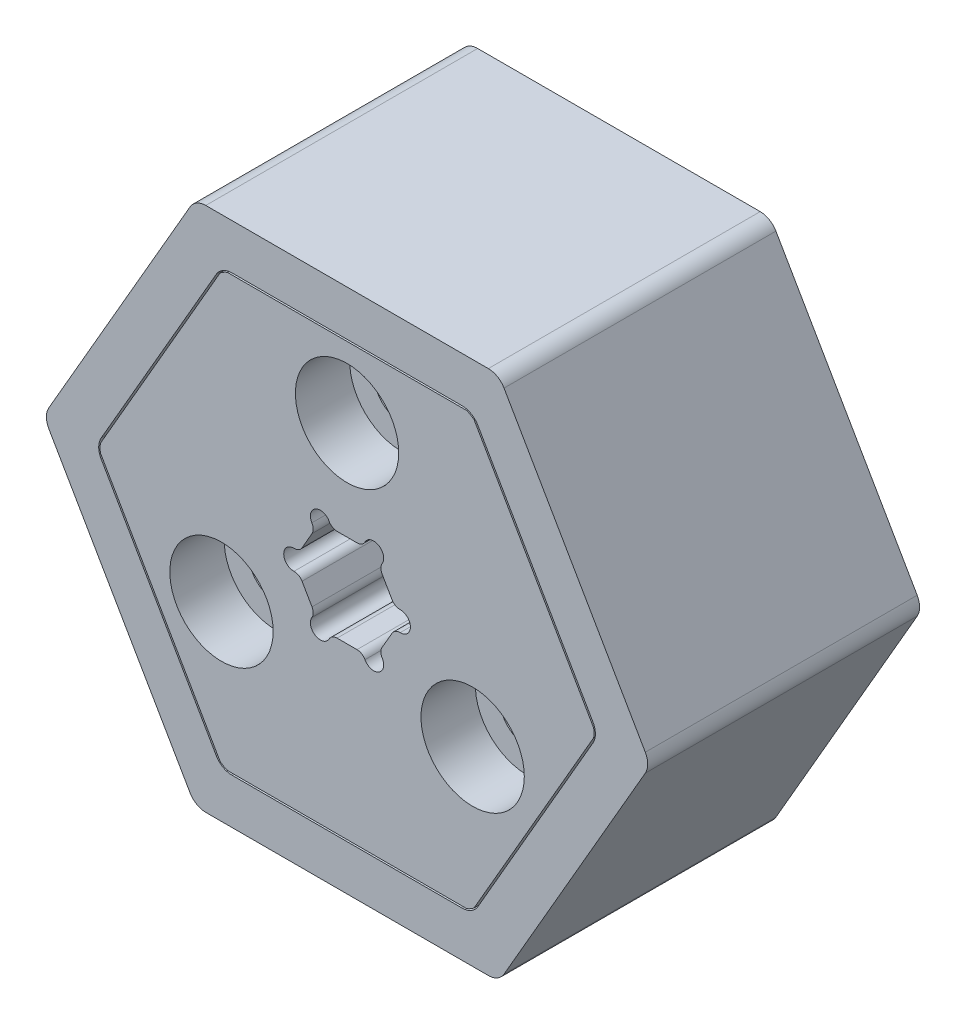
SolidWorks part; units mm, degrees
ref_plane "前视基准面" through (0, 0, 0) normal (0, 0, 1) x (1, 0, 0)
ref_plane "上视基准面" through (0, 0, 0) normal (0, 1, 0) x (1, 0, 0)
ref_plane "右视基准面" through (0, 0, 0) normal (1, 0, 0) x (0, 0, -1)
other "Configuration Table"
sketch "草图1" plane through (0, 0, 0) normal (0, 0, 1) x (1, 0, 0)
  line L0 (0, 6.5) -> (0, 0) construction
  line L1 (0, 0) -> (0, -6.5) construction
  line L3 (8.3716, 14.5) -> (-8.3716, 14.5)
  line L4 (-8.3716, 14.5) -> (-16.7432, 0)
  line L5 (-16.7432, 0) -> (-8.3716, -14.5)
  line L6 (-8.3716, -14.5) -> (8.3716, -14.5)
  line L7 (8.3716, -14.5) -> (16.7432, 0)
  line L8 (16.7432, 0) -> (8.3716, 14.5)
  line L9 (7.2169, 12.5) -> (-7.2169, 12.5)
  line L10 (-7.2169, 12.5) -> (-14.4338, 0)
  line L11 (-14.4338, 0) -> (-7.2169, -12.5)
  line L12 (-7.2169, -12.5) -> (7.2169, -12.5)
  line L13 (7.2169, -12.5) -> (14.4338, 0)
  line L14 (14.4338, 0) -> (7.2169, 12.5)
  circle A1 centre (0, 6.5) radius 1.5
  circle A2 centre (0, -6.5) radius 1.5
  circle A3 centre (0, 0) radius 14.5 construction
  circle A4 centre (0, 0) radius 12.5 construction
  dimension "D1" = 3
  dimension "D2" = 13
  dimension "D3" = 29
  dimension "D4" = 2
extrude "凸台-拉伸1" add sketch "草图1" along normal blind 2 contours L13 L14 L9 L10 L11 L12 A2 A1 | L7 L8 L3 L4 L5 L6 L14 L13 L12 L11 L10 L9
sketch "草图2" plane through (0, 0, 2) normal (0, 0, 1) x (1, 0, 0)
  line L1 (5.7735, 10) -> (-5.7735, 10)
  line L2 (-5.7735, 10) -> (-11.547, 0)
  line L3 (-11.547, 0) -> (-5.7735, -10)
  line L4 (-5.7735, -10) -> (5.7735, -10)
  line L5 (5.7735, -10) -> (11.547, 0)
  line L6 (11.547, 0) -> (5.7735, 10)
  line L7 (4.6188, 8) -> (-4.6188, 8)
  line L8 (-4.6188, 8) -> (-9.2376, 0)
  line L9 (-9.2376, 0) -> (-4.6188, -8)
  line L10 (-4.6188, -8) -> (4.6188, -8)
  line L11 (4.6188, -8) -> (9.2376, 0)
  line L12 (9.2376, 0) -> (4.6188, 8)
  circle A0 centre (0, 0) radius 10 construction
  circle A1 centre (0, 0) radius 8 construction
  dimension "D1" = 2
sketch "草图3" plane through (0, 0, 2) normal (0, 0, 1) x (1, 0, 0)
  line L1 (6.9282, 12) -> (-6.9282, 12)
  line L2 (-6.9282, 12) -> (-13.8564, 0)
  line L3 (-13.8564, 0) -> (-6.9282, -12)
  line L4 (-6.9282, -12) -> (6.9282, -12)
  line L5 (6.9282, -12) -> (13.8564, 0)
  line L6 (13.8564, 0) -> (6.9282, 12)
  line L12 (8.3716, -14.5) -> (16.7432, 0)
  line L13 (16.7432, 0) -> (8.3716, 14.5)
  line L14 (8.3716, 14.5) -> (-8.3716, 14.5)
  line L15 (-8.3716, 14.5) -> (-16.7432, 0)
  line L16 (-16.7432, 0) -> (-8.3716, -14.5)
  line L17 (-8.3716, -14.5) -> (8.3716, -14.5)
  line L18 (8.3716, -14.5) -> (16.7432, 0)
  line L19 (16.7432, 0) -> (8.3716, 14.5)
  line L20 (8.3716, 14.5) -> (-8.3716, 14.5)
  line L21 (-8.3716, 14.5) -> (-16.7432, 0)
  line L22 (-16.7432, 0) -> (-8.3716, -14.5)
  line L23 (-8.3716, -14.5) -> (8.3716, -14.5)
  circle A0 centre (0, 0) radius 12 construction
  dimension "D2" = 2.5
  dimension "D1" = 0
extrude "凸台-拉伸2" add sketch "草图3" along normal blind 13
sketch "草图4" plane through (0, 0, 2) normal (0, 0, 1) x (1, 0, 0)
  line L0 (0, 6.5) -> (0, -6.5) construction
  line L1 (3, 6.5) -> (3, -6.5)
  line L2 (-3, 6.5) -> (-3, -6.5)
  line L6 (13.8564, 0) -> (6.9282, 12)
  line L7 (6.9282, 12) -> (-6.9282, 12)
  line L8 (-6.9282, 12) -> (-13.8564, 0)
  line L9 (-13.8564, 0) -> (-6.9282, -12)
  line L10 (-6.9282, -12) -> (6.9282, -12)
  line L11 (6.9282, -12) -> (13.8564, 0)
  line L12 (13.8564, 0) -> (6.9282, 12)
  line L13 (6.9282, 12) -> (-6.9282, 12)
  line L14 (-6.9282, 12) -> (-13.8564, 0)
  line L15 (-13.8564, 0) -> (-6.9282, -12)
  line L16 (-6.9282, -12) -> (6.9282, -12)
  line L17 (6.9282, -12) -> (13.8564, 0)
  circle A1 centre (0, -6.5) radius 1.5
  circle A2 centre (0, -6.5) radius 1.5 construction
  circle A3 centre (0, 6.5) radius 1.5
  circle A4 centre (0, 6.5) radius 1.5 construction
  arc A6 (3, 6.5) -> (-3, 6.5) centre (0, 6.5) ccw
  arc A7 (-3, -6.5) -> (3, -6.5) centre (0, -6.5) ccw
  point P8 (0, 0)
  dimension "D4" = 3
  dimension "D1" = 0
  dimension "D2" = 0
  dimension "D3" = 0
extrude "凸台-拉伸3" add sketch "草图4" along normal blind 3
sketch "草图5" plane through (0, 0, 5) normal (0, 0, 1) x (1, 0, 0)
  line L1 (1.4722, 2.55) -> (-1.4722, 2.55)
  line L2 (-1.4722, 2.55) -> (-2.9445, 0)
  line L3 (-2.9445, 0) -> (-1.4722, -2.55)
  line L4 (-1.4722, -2.55) -> (1.4722, -2.55)
  line L5 (1.4722, -2.55) -> (2.9445, 0)
  line L6 (6.9282, -12) -> (13.8564, 0)
  line L7 (13.8564, 0) -> (6.9282, 12)
  line L8 (6.9282, 12) -> (-6.9282, 12)
  line L9 (-6.9282, 12) -> (-13.8564, 0)
  line L10 (-13.8564, 0) -> (-6.9282, -12)
  line L11 (-6.9282, -12) -> (6.9282, -12)
  line L12 (6.9282, -12) -> (13.8564, 0)
  line L13 (13.8564, 0) -> (6.9282, 12)
  line L14 (6.9282, 12) -> (-6.9282, 12)
  line L15 (-6.9282, 12) -> (-13.8564, 0)
  line L16 (-13.8564, 0) -> (-6.9282, -12)
  line L17 (-6.9282, -12) -> (6.9282, -12)
  line L18 (2.9445, 0) -> (1.4722, 2.55)
  circle A0 centre (0, 0) radius 2.55 construction
  dimension "D2" = 5.1
  dimension "D1" = 0
extrude "凸台-拉伸4" add sketch "草图5" along normal blind 10 separate body
sketch "草图6" plane through (-12.5574, -7.25, 0) normal (-0.866, -0.5, 0) x (0, 0, 1)
  line L0 (15, 8.3716) -> (15, -8.3716) construction
  line L1 (0, 0) -> (10, 0) construction
  line L2 (0, 8.3716) -> (0, -8.3716) construction
  circle A0 centre (10, 0) radius 1.5
  dimension "D1" = 3
  dimension "D2" = 5
sketch "草图8" plane through (0, 0, 0) normal (0, 0, -1) x (-1, 0, 0)
  circle A0 centre (0, 0) radius 3.75
  dimension "D1" = 7.5
extrude "切除-拉伸2" cut sketch "草图8" against normal blind 10
fillet "圆角1" radius 1 16 edges at (-3, 2.25, 3.5) (-3, -2.25, 3.5) (3, -2.25, 3.5) (3, 2.25, 3.5) (-13.8564, 0, 10) (-6.9282, -12, 10) (6.9282, -12, 10) (13.8564, 0, 10) (6.9282, 12, 10) (-6.9282, 12, 10) (-8.3716, -14.5, 7.5) (-8.3716, 14.5, 7.5) (8.3716, 14.5, 7.5) (16.7432, 0, 7.5) (8.3716, -14.5, 7.5) (-16.7432, 0, 7.5)
fillet "圆角2" radius 1.5 6 edges at (-6.9282, -12, 10) (-13.8564, 0, 10) (6.9282, 12, 10) (13.8564, 0, 10) (6.9282, -12, 10) (-6.9282, 12, 10)
sketch "草图9" plane through (0, 0, 15) normal (0, 0, 1) x (1, 0, 0)
  line L0 (0, 0) -> (1.4722, 2.55) construction
  line L3 (-2.9445, 0) -> (-1.4722, -2.55) construction
  circle A0 centre (1.4722, 2.55) radius 0.55
  circle A1 centre (2.9445, 0) radius 0.55
  circle A2 centre (1.4722, -2.55) radius 0.55
  circle A3 centre (-1.4722, -2.55) radius 0.55
  circle A4 centre (-2.9445, 0) radius 0.55
  circle A5 centre (-1.4722, 2.55) radius 0.55
  dimension "D1" = 1.1
extrude "切除-拉伸3" cut sketch "草图9" against normal blind 10
fillet "圆角3" radius 0.5 12 edges at (0.9222, 2.55, 10) (1.7472, 2.0737, 10) (2.6695, 0.4763, 10) (2.6695, -0.4763, 10) (1.7472, -2.0737, 10) (0.9222, -2.55, 10) (-0.9222, -2.55, 10) (-1.7472, -2.0737, 10) (-2.6695, -0.4763, 10) (-2.6695, 0.4763, 10) (-1.7472, 2.0737, 10) (-0.9222, 2.55, 10)
sketch "草图10" plane through (0, 0, 15) normal (0, 0, 1) x (1, 0, 0)
  circle A0 centre (0, 0) radius 8 construction
  circle A1 centre (0, 8) radius 1.25
  circle A2 centre (6.9282, -4) radius 1.25
  circle A3 centre (-6.9282, -4) radius 1.25
  point P14 (0, 0)
  dimension "D1" = 2.5
  dimension "D2" = 16
  dimension "D3" = 3
extrude "切除-拉伸4" cut sketch "草图10" against normal blind 10
sketch "草图11" plane through (0, 0, 15) normal (0, 0, 1) x (1, 0, 0)
  line L6 (-13.4234, -0.75) -> (-7.3612, -11.25)
  line L7 (-6.0622, -12) -> (6.0622, -12)
  line L8 (7.3612, -11.25) -> (13.4234, -0.75)
  line L9 (13.4234, 0.75) -> (7.3612, 11.25)
  line L10 (6.0622, 12) -> (-6.0622, 12)
  line L11 (-7.3612, 11.25) -> (-13.4234, 0.75)
  line L12 (-13.4234, -0.75) -> (-7.3612, -11.25)
  line L13 (-6.0622, -12) -> (6.0622, -12)
  line L14 (7.3612, -11.25) -> (13.4234, -0.75)
  line L15 (13.4234, 0.75) -> (7.3612, 11.25)
  line L16 (6.0622, 12) -> (-6.0622, 12)
  line L17 (-7.3612, 11.25) -> (-13.4234, 0.75)
  line L18 (0.5489, 2.55) -> (-0.5489, 2.55)
  line L19 (2.4828, 0.7996) -> (1.9339, 1.7504)
  line L20 (1.9339, -1.7504) -> (2.4828, -0.7996)
  line L21 (-0.5489, -2.55) -> (0.5489, -2.55)
  line L22 (-2.4828, -0.7996) -> (-1.9339, -1.7504)
  line L23 (-1.9339, 1.7504) -> (-2.4828, 0.7996)
  line L24 (0.5489, 2.55) -> (-0.5489, 2.55)
  line L25 (2.4828, 0.7996) -> (1.9339, 1.7504)
  line L26 (1.9339, -1.7504) -> (2.4828, -0.7996)
  line L27 (-0.5489, -2.55) -> (0.5489, -2.55)
  line L28 (-2.4828, -0.7996) -> (-1.9339, -1.7504)
  line L29 (-1.9339, 1.7504) -> (-2.4828, 0.7996)
  circle A1 centre (-6.9282, -4) radius 1.25
  circle A2 centre (-6.9282, -4) radius 1.25
  circle A3 centre (6.9282, -4) radius 1.25
  circle A4 centre (6.9282, -4) radius 1.25
  circle A5 centre (0, 8) radius 1.25
  arc A6 (-7.3612, -11.25) -> (-6.0622, -12) centre (-6.0622, -10.5) ccw
  arc A7 (6.0622, -12) -> (7.3612, -11.25) centre (6.0622, -10.5) ccw
  arc A8 (13.4234, -0.75) -> (13.4234, 0.75) centre (12.1244, 0) ccw
  arc A9 (7.3612, 11.25) -> (6.0622, 12) centre (6.0622, 10.5) ccw
  arc A10 (-6.0622, 12) -> (-7.3612, 11.25) centre (-6.0622, 10.5) ccw
  arc A11 (-13.4234, 0.75) -> (-13.4234, -0.75) centre (-12.1244, 0) ccw
  arc A12 (-7.3612, -11.25) -> (-6.0622, -12) centre (-6.0622, -10.5) ccw
  arc A13 (6.0622, -12) -> (7.3612, -11.25) centre (6.0622, -10.5) ccw
  arc A14 (13.4234, -0.75) -> (13.4234, 0.75) centre (12.1244, 0) ccw
  arc A15 (7.3612, 11.25) -> (6.0622, 12) centre (6.0622, 10.5) ccw
  arc A16 (-6.0622, 12) -> (-7.3612, 11.25) centre (-6.0622, 10.5) ccw
  arc A17 (-13.4234, 0.75) -> (-13.4234, -0.75) centre (-12.1244, 0) ccw
  circle A18 centre (0, 8) radius 1.25
  arc A30 (0.5489, 2.55) -> (0.9886, 2.8119) centre (0.5489, 3.05) ccw
  arc A31 (1.9409, 2.2621) -> (0.9886, 2.8119) centre (1.4722, 2.55) ccw
  arc A32 (1.9409, 2.2621) -> (1.9339, 1.7504) centre (2.3669, 2.0004) ccw
  arc A33 (2.4828, 0.7996) -> (2.9295, 0.5498) centre (2.9158, 1.0496) ccw
  arc A34 (2.9295, -0.5498) -> (2.9295, 0.5498) centre (2.9445, 0) ccw
  arc A35 (2.9295, -0.5498) -> (2.4828, -0.7996) centre (2.9158, -1.0496) ccw
  arc A36 (1.9339, -1.7504) -> (1.9409, -2.2621) centre (2.3669, -2.0004) ccw
  arc A37 (0.9886, -2.8119) -> (1.9409, -2.2621) centre (1.4722, -2.55) ccw
  arc A38 (0.9886, -2.8119) -> (0.5489, -2.55) centre (0.5489, -3.05) ccw
  arc A39 (-0.5489, -2.55) -> (-0.9886, -2.8119) centre (-0.5489, -3.05) ccw
  arc A40 (-1.9409, -2.2621) -> (-0.9886, -2.8119) centre (-1.4722, -2.55) ccw
  arc A41 (-1.9409, -2.2621) -> (-1.9339, -1.7504) centre (-2.3669, -2.0004) ccw
  arc A42 (-2.4828, -0.7996) -> (-2.9295, -0.5498) centre (-2.9158, -1.0496) ccw
  arc A43 (-2.9295, 0.5498) -> (-2.9295, -0.5498) centre (-2.9445, 0) ccw
  arc A44 (-2.9295, 0.5498) -> (-2.4828, 0.7996) centre (-2.9158, 1.0496) ccw
  arc A45 (-1.9339, 1.7504) -> (-1.9409, 2.2621) centre (-2.3669, 2.0004) ccw
  arc A46 (-0.9886, 2.8119) -> (-1.9409, 2.2621) centre (-1.4722, 2.55) ccw
  arc A47 (-0.9886, 2.8119) -> (-0.5489, 2.55) centre (-0.5489, 3.05) ccw
  arc A48 (0.5489, 2.55) -> (0.9886, 2.8119) centre (0.5489, 3.05) ccw
  arc A49 (1.9409, 2.2621) -> (0.9886, 2.8119) centre (1.4722, 2.55) ccw
  arc A50 (1.9409, 2.2621) -> (1.9339, 1.7504) centre (2.3669, 2.0004) ccw
  arc A51 (2.4828, 0.7996) -> (2.9295, 0.5498) centre (2.9158, 1.0496) ccw
  arc A52 (2.9295, -0.5498) -> (2.9295, 0.5498) centre (2.9445, 0) ccw
  arc A53 (2.9295, -0.5498) -> (2.4828, -0.7996) centre (2.9158, -1.0496) ccw
  arc A54 (1.9339, -1.7504) -> (1.9409, -2.2621) centre (2.3669, -2.0004) ccw
  arc A55 (0.9886, -2.8119) -> (1.9409, -2.2621) centre (1.4722, -2.55) ccw
  arc A56 (0.9886, -2.8119) -> (0.5489, -2.55) centre (0.5489, -3.05) ccw
  arc A57 (-0.5489, -2.55) -> (-0.9886, -2.8119) centre (-0.5489, -3.05) ccw
  arc A58 (-1.9409, -2.2621) -> (-0.9886, -2.8119) centre (-1.4722, -2.55) ccw
  arc A59 (-1.9409, -2.2621) -> (-1.9339, -1.7504) centre (-2.3669, -2.0004) ccw
  arc A60 (-2.4828, -0.7996) -> (-2.9295, -0.5498) centre (-2.9158, -1.0496) ccw
  arc A61 (-2.9295, 0.5498) -> (-2.9295, -0.5498) centre (-2.9445, 0) ccw
  arc A62 (-2.9295, 0.5498) -> (-2.4828, 0.7996) centre (-2.9158, 1.0496) ccw
  arc A63 (-1.9339, 1.7504) -> (-1.9409, 2.2621) centre (-2.3669, 2.0004) ccw
  arc A64 (-0.9886, 2.8119) -> (-1.9409, 2.2621) centre (-1.4722, 2.55) ccw
  arc A65 (-0.9886, 2.8119) -> (-0.5489, 2.55) centre (-0.5489, 3.05) ccw
  dimension "D1" = 0
  dimension "D2" = 0
  dimension "D3" = 0
  dimension "D4" = 0
  dimension "D5" = 0
extrude "切除-拉伸5" cut sketch "草图11" against normal blind 5
sketch "草图12" plane through (0, 0, 10) normal (0, 0, 1) x (1, 0, 0)
  line L6 (-13.4234, -0.75) -> (-7.3612, -11.25)
  line L7 (-6.0622, -12) -> (6.0622, -12)
  line L8 (7.3612, -11.25) -> (13.4234, -0.75)
  line L9 (13.4234, 0.75) -> (7.3612, 11.25)
  line L10 (6.0622, 12) -> (-6.0622, 12)
  line L11 (-7.3612, 11.25) -> (-13.4234, 0.75)
  line L12 (-13.4234, -0.75) -> (-7.3612, -11.25)
  line L13 (-6.0622, -12) -> (6.0622, -12)
  line L14 (7.3612, -11.25) -> (13.4234, -0.75)
  line L15 (13.4234, 0.75) -> (7.3612, 11.25)
  line L16 (6.0622, 12) -> (-6.0622, 12)
  line L17 (-7.3612, 11.25) -> (-13.4234, 0.75)
  line L18 (0.5489, 2.55) -> (-0.5489, 2.55)
  line L19 (2.4828, 0.7996) -> (1.9339, 1.7504)
  line L20 (1.9339, -1.7504) -> (2.4828, -0.7996)
  line L21 (-0.5489, -2.55) -> (0.5489, -2.55)
  line L22 (-2.4828, -0.7996) -> (-1.9339, -1.7504)
  line L23 (-1.9339, 1.7504) -> (-2.4828, 0.7996)
  line L24 (0.5489, 2.55) -> (-0.5489, 2.55)
  line L25 (2.4828, 0.7996) -> (1.9339, 1.7504)
  line L26 (1.9339, -1.7504) -> (2.4828, -0.7996)
  line L27 (-0.5489, -2.55) -> (0.5489, -2.55)
  line L28 (-2.4828, -0.7996) -> (-1.9339, -1.7504)
  line L29 (-1.9339, 1.7504) -> (-2.4828, 0.7996)
  circle A0 centre (0, 8) radius 1.5
  circle A1 centre (6.9282, -4) radius 1.5
  circle A2 centre (-6.9282, -4) radius 1.5
  circle A4 centre (-6.9282, -4) radius 1.25
  circle A5 centre (-6.9282, -4) radius 1.25 construction
  arc A6 (-13.4234, 0.75) -> (-13.4234, -0.75) centre (-12.1244, 0) ccw
  arc A7 (-7.3612, -11.25) -> (-6.0622, -12) centre (-6.0622, -10.5) ccw
  arc A8 (6.0622, -12) -> (7.3612, -11.25) centre (6.0622, -10.5) ccw
  arc A9 (13.4234, -0.75) -> (13.4234, 0.75) centre (12.1244, 0) ccw
  arc A10 (7.3612, 11.25) -> (6.0622, 12) centre (6.0622, 10.5) ccw
  arc A11 (-6.0622, 12) -> (-7.3612, 11.25) centre (-6.0622, 10.5) ccw
  arc A12 (-13.4234, 0.75) -> (-13.4234, -0.75) centre (-12.1244, 0) ccw
  arc A13 (-7.3612, -11.25) -> (-6.0622, -12) centre (-6.0622, -10.5) ccw
  arc A14 (6.0622, -12) -> (7.3612, -11.25) centre (6.0622, -10.5) ccw
  arc A15 (13.4234, -0.75) -> (13.4234, 0.75) centre (12.1244, 0) ccw
  arc A16 (7.3612, 11.25) -> (6.0622, 12) centre (6.0622, 10.5) ccw
  arc A17 (-6.0622, 12) -> (-7.3612, 11.25) centre (-6.0622, 10.5) ccw
  circle A18 centre (6.9282, -4) radius 1.25
  circle A19 centre (6.9282, -4) radius 1.25 construction
  circle A20 centre (0, 8) radius 1.25
  circle A21 centre (0, 8) radius 1.25 construction
  arc A33 (0.5489, 2.55) -> (0.9886, 2.8119) centre (0.5489, 3.05) ccw
  arc A34 (1.9409, 2.2621) -> (0.9886, 2.8119) centre (1.4722, 2.55) ccw
  arc A35 (1.9409, 2.2621) -> (1.9339, 1.7504) centre (2.3669, 2.0004) ccw
  arc A36 (2.4828, 0.7996) -> (2.9295, 0.5498) centre (2.9158, 1.0496) ccw
  arc A37 (2.9295, -0.5498) -> (2.9295, 0.5498) centre (2.9445, 0) ccw
  arc A38 (2.9295, -0.5498) -> (2.4828, -0.7996) centre (2.9158, -1.0496) ccw
  arc A39 (1.9339, -1.7504) -> (1.9409, -2.2621) centre (2.3669, -2.0004) ccw
  arc A40 (0.9886, -2.8119) -> (1.9409, -2.2621) centre (1.4722, -2.55) ccw
  arc A41 (0.9886, -2.8119) -> (0.5489, -2.55) centre (0.5489, -3.05) ccw
  arc A42 (-0.5489, -2.55) -> (-0.9886, -2.8119) centre (-0.5489, -3.05) ccw
  arc A43 (-1.9409, -2.2621) -> (-0.9886, -2.8119) centre (-1.4722, -2.55) ccw
  arc A44 (-1.9409, -2.2621) -> (-1.9339, -1.7504) centre (-2.3669, -2.0004) ccw
  arc A45 (-2.4828, -0.7996) -> (-2.9295, -0.5498) centre (-2.9158, -1.0496) ccw
  arc A46 (-2.9295, 0.5498) -> (-2.9295, -0.5498) centre (-2.9445, 0) ccw
  arc A47 (-2.9295, 0.5498) -> (-2.4828, 0.7996) centre (-2.9158, 1.0496) ccw
  arc A48 (-1.9339, 1.7504) -> (-1.9409, 2.2621) centre (-2.3669, 2.0004) ccw
  arc A49 (-0.9886, 2.8119) -> (-1.9409, 2.2621) centre (-1.4722, 2.55) ccw
  arc A50 (-0.9886, 2.8119) -> (-0.5489, 2.55) centre (-0.5489, 3.05) ccw
  arc A51 (0.5489, 2.55) -> (0.9886, 2.8119) centre (0.5489, 3.05) ccw
  arc A52 (1.9409, 2.2621) -> (0.9886, 2.8119) centre (1.4722, 2.55) ccw
  arc A53 (1.9409, 2.2621) -> (1.9339, 1.7504) centre (2.3669, 2.0004) ccw
  arc A54 (2.4828, 0.7996) -> (2.9295, 0.5498) centre (2.9158, 1.0496) ccw
  arc A55 (2.9295, -0.5498) -> (2.9295, 0.5498) centre (2.9445, 0) ccw
  arc A56 (2.9295, -0.5498) -> (2.4828, -0.7996) centre (2.9158, -1.0496) ccw
  arc A57 (1.9339, -1.7504) -> (1.9409, -2.2621) centre (2.3669, -2.0004) ccw
  arc A58 (0.9886, -2.8119) -> (1.9409, -2.2621) centre (1.4722, -2.55) ccw
  arc A59 (0.9886, -2.8119) -> (0.5489, -2.55) centre (0.5489, -3.05) ccw
  arc A60 (-0.5489, -2.55) -> (-0.9886, -2.8119) centre (-0.5489, -3.05) ccw
  arc A61 (-1.9409, -2.2621) -> (-0.9886, -2.8119) centre (-1.4722, -2.55) ccw
  arc A62 (-1.9409, -2.2621) -> (-1.9339, -1.7504) centre (-2.3669, -2.0004) ccw
  arc A63 (-2.4828, -0.7996) -> (-2.9295, -0.5498) centre (-2.9158, -1.0496) ccw
  arc A64 (-2.9295, 0.5498) -> (-2.9295, -0.5498) centre (-2.9445, 0) ccw
  arc A65 (-2.9295, 0.5498) -> (-2.4828, 0.7996) centre (-2.9158, 1.0496) ccw
  arc A66 (-1.9339, 1.7504) -> (-1.9409, 2.2621) centre (-2.3669, 2.0004) ccw
  arc A67 (-0.9886, 2.8119) -> (-1.9409, 2.2621) centre (-1.4722, 2.55) ccw
  arc A68 (-0.9886, 2.8119) -> (-0.5489, 2.55) centre (-0.5489, 3.05) ccw
  dimension "D2" = 3
  dimension "D1" = 0
  dimension "D3" = 0
  dimension "D4" = 0
  dimension "D5" = 0
  dimension "D6" = 0
extrude "凸台-拉伸5" add sketch "草图12" along normal blind 5 separate body
sketch "草图14" plane through (0, 0, 15) normal (0, 0, 1) x (1, 0, 0)
  circle A0 centre (0, 8) radius 2.85
  circle A2 centre (6.9282, -4) radius 2.85
  circle A3 centre (-6.9282, -4) radius 2.85
  dimension "D1" = 5.7
extrude "切除-拉伸6" cut sketch "草图14" against normal blind 3
sketch "草图15" plane through (0, 0, 15) normal (0, 0, 1) x (1, 0, 0)
  line L0 (0.5489, 2.55) -> (-0.5489, 2.55) construction
  line L1 (1.5877, 2.75) -> (-1.5877, 2.75)
  line L2 (-1.5877, 2.75) -> (-3.1754, 0)
  line L3 (-3.1754, 0) -> (-1.5877, -2.75)
  line L4 (-1.5877, -2.75) -> (1.5877, -2.75)
  line L5 (1.5877, -2.75) -> (3.1754, 0)
  line L6 (3.1754, 0) -> (1.5877, 2.75)
  line L8 (6.8127, 11.8) -> (-6.8127, 11.8)
  line L9 (-6.8127, 11.8) -> (-13.6255, 0)
  line L10 (-13.6255, 0) -> (-6.8127, -11.8)
  line L11 (-6.8127, -11.8) -> (6.8127, -11.8)
  line L12 (6.8127, -11.8) -> (13.6255, 0)
  line L13 (13.6255, 0) -> (6.8127, 11.8)
  line L14 (6.0622, 12) -> (-6.0622, 12) construction
  line L21 (-13.4234, -0.75) -> (-7.3612, -11.25)
  line L22 (-6.0622, -12) -> (6.0622, -12)
  line L23 (7.3612, -11.25) -> (13.4234, -0.75)
  line L24 (13.4234, 0.75) -> (7.3612, 11.25)
  line L25 (6.0622, 12) -> (-6.0622, 12)
  line L26 (-7.3612, 11.25) -> (-13.4234, 0.75)
  line L27 (-13.4234, -0.75) -> (-7.3612, -11.25)
  line L28 (-6.0622, -12) -> (6.0622, -12)
  line L29 (7.3612, -11.25) -> (13.4234, -0.75)
  line L30 (13.4234, 0.75) -> (7.3612, 11.25)
  line L31 (6.0622, 12) -> (-6.0622, 12)
  line L32 (-7.3612, 11.25) -> (-13.4234, 0.75)
  circle A0 centre (0, 0) radius 2.75 construction
  circle A1 centre (0, 0) radius 11.8 construction
  arc A8 (-13.4234, 0.75) -> (-13.4234, -0.75) centre (-12.1244, 0) ccw
  arc A9 (-7.3612, -11.25) -> (-6.0622, -12) centre (-6.0622, -10.5) ccw
  arc A10 (6.0622, -12) -> (7.3612, -11.25) centre (6.0622, -10.5) ccw
  arc A11 (13.4234, -0.75) -> (13.4234, 0.75) centre (12.1244, 0) ccw
  arc A12 (7.3612, 11.25) -> (6.0622, 12) centre (6.0622, 10.5) ccw
  arc A13 (-6.0622, 12) -> (-7.3612, 11.25) centre (-6.0622, 10.5) ccw
  arc A14 (-13.4234, 0.75) -> (-13.4234, -0.75) centre (-12.1244, 0) ccw
  arc A15 (-7.3612, -11.25) -> (-6.0622, -12) centre (-6.0622, -10.5) ccw
  arc A16 (6.0622, -12) -> (7.3612, -11.25) centre (6.0622, -10.5) ccw
  arc A17 (13.4234, -0.75) -> (13.4234, 0.75) centre (12.1244, 0) ccw
  arc A18 (7.3612, 11.25) -> (6.0622, 12) centre (6.0622, 10.5) ccw
  arc A19 (-6.0622, 12) -> (-7.3612, 11.25) centre (-6.0622, 10.5) ccw
  arc M18 (-13.4234, 0.75) -> (-13.4234, -0.75) centre (-12.1244, 0) ccw
  line M19 (-13.4234, -0.75) -> (-7.3612, -11.25)
  arc M20 (-7.3612, -11.25) -> (-6.0622, -12) centre (-6.0622, -10.5) ccw
  line M21 (-6.0622, -12) -> (6.0622, -12)
  arc M22 (6.0622, -12) -> (7.3612, -11.25) centre (6.0622, -10.5) ccw
  line M23 (7.3612, -11.25) -> (13.4234, -0.75)
  arc M24 (13.4234, -0.75) -> (13.4234, 0.75) centre (12.1244, 0) ccw
  line M25 (13.4234, 0.75) -> (7.3612, 11.25)
  arc M26 (7.3612, 11.25) -> (6.0622, 12) centre (6.0622, 10.5) ccw
  line M27 (6.0622, 12) -> (-6.0622, 12)
  arc M28 (-6.0622, 12) -> (-7.3612, 11.25) centre (-6.0622, 10.5) ccw
  line M29 (-7.3612, 11.25) -> (-13.4234, 0.75)
  arc M31 (-0.9886, 2.8119) -> (-0.5489, 2.55) centre (-0.5489, 3.05) ccw
  line M32 (-0.5489, 2.55) -> (0.5489, 2.55)
  arc M33 (0.5489, 2.55) -> (0.9886, 2.8119) centre (0.5489, 3.05) ccw
  arc M35 (1.9409, 2.2621) -> (1.9339, 1.7504) centre (2.3669, 2.0004) ccw
  line M36 (1.9339, 1.7504) -> (2.4828, 0.7996)
  arc M37 (2.4828, 0.7996) -> (2.9295, 0.5498) centre (2.9158, 1.0496) ccw
  arc M39 (2.9295, -0.5498) -> (2.4828, -0.7996) centre (2.9158, -1.0496) ccw
  line M40 (2.4828, -0.7996) -> (1.9339, -1.7504)
  arc M41 (1.9339, -1.7504) -> (1.9409, -2.2621) centre (2.3669, -2.0004) ccw
  arc M47 (-1.9409, -2.2621) -> (-1.9339, -1.7504) centre (-2.3669, -2.0004) ccw
  line M48 (-1.9339, -1.7504) -> (-2.4828, -0.7996)
  arc M49 (-2.4828, -0.7996) -> (-2.9295, -0.5498) centre (-2.9158, -1.0496) ccw
  arc M51 (-2.9295, 0.5498) -> (-2.4828, 0.7996) centre (-2.9158, 1.0496) ccw
  line M52 (-2.4828, 0.7996) -> (-1.9339, 1.7504)
  arc M53 (-1.9339, 1.7504) -> (-1.9409, 2.2621) centre (-2.3669, 2.0004) ccw
  dimension "D1" = 0.2
  dimension "D2" = 0.2
  dimension "D3" = 0
extrude "切除-拉伸7" [suppressed] cut sketch "草图15" against normal blind 10 contours L8 M26 M27 M28 | L9 M28 M29 M18 | L13 M24 M25 M26 | L12 M22 M23 M24 | L11 M20 M21 M22 | L10 M18 M19 M20 | L3 M49 M47 M48 | L2 M53 M51 M52 | L1 M33 M31 M32 | L6 M37 M35 M36 | L5 M41 M39 M40
sketch "草图16" plane through (0, 0, 15) normal (0, 0, 1) x (1, 0, 0)
  line L1 (6.8705, 11.9) -> (-6.8705, 11.9)
  line L2 (-6.8705, 11.9) -> (-13.7409, 0)
  line L3 (-13.7409, 0) -> (-6.8705, -11.9)
  line L4 (-6.8705, -11.9) -> (6.8705, -11.9)
  line L5 (6.8705, -11.9) -> (13.7409, 0)
  line L6 (-13.4234, -0.75) -> (-7.3612, -11.25)
  line L7 (-6.0622, -12) -> (6.0622, -12)
  line L8 (7.3612, -11.25) -> (13.4234, -0.75)
  line L9 (13.4234, 0.75) -> (7.3612, 11.25)
  line L10 (6.0622, 12) -> (-6.0622, 12)
  line L11 (-7.3612, 11.25) -> (-13.4234, 0.75)
  line L12 (-13.4234, -0.75) -> (-7.3612, -11.25)
  line L13 (-6.0622, -12) -> (6.0622, -12)
  line L14 (7.3612, -11.25) -> (13.4234, -0.75)
  line L15 (13.4234, 0.75) -> (7.3612, 11.25)
  line L16 (6.0622, 12) -> (-6.0622, 12)
  line L17 (-7.3612, 11.25) -> (-13.4234, 0.75)
  line L18 (13.7409, 0) -> (6.8705, 11.9)
  circle A0 centre (0, 0) radius 11.9 construction
  arc A6 (-13.4234, 0.75) -> (-13.4234, -0.75) centre (-12.1244, 0) ccw
  arc A7 (-7.3612, -11.25) -> (-6.0622, -12) centre (-6.0622, -10.5) ccw
  arc A8 (6.0622, -12) -> (7.3612, -11.25) centre (6.0622, -10.5) ccw
  arc A9 (13.4234, -0.75) -> (13.4234, 0.75) centre (12.1244, 0) ccw
  arc A10 (7.3612, 11.25) -> (6.0622, 12) centre (6.0622, 10.5) ccw
  arc A11 (-6.0622, 12) -> (-7.3612, 11.25) centre (-6.0622, 10.5) ccw
  arc A12 (-13.4234, 0.75) -> (-13.4234, -0.75) centre (-12.1244, 0) ccw
  arc A13 (-7.3612, -11.25) -> (-6.0622, -12) centre (-6.0622, -10.5) ccw
  arc A14 (6.0622, -12) -> (7.3612, -11.25) centre (6.0622, -10.5) ccw
  arc A15 (13.4234, -0.75) -> (13.4234, 0.75) centre (12.1244, 0) ccw
  arc A16 (7.3612, 11.25) -> (6.0622, 12) centre (6.0622, 10.5) ccw
  arc A17 (-6.0622, 12) -> (-7.3612, 11.25) centre (-6.0622, 10.5) ccw
  arc M17 (-13.4234, 0.75) -> (-13.4234, -0.75) centre (-12.1244, 0) ccw
  line M18 (-13.4234, -0.75) -> (-7.3612, -11.25)
  arc M19 (-7.3612, -11.25) -> (-6.0622, -12) centre (-6.0622, -10.5) ccw
  line M20 (-6.0622, -12) -> (6.0622, -12)
  arc M21 (6.0622, -12) -> (7.3612, -11.25) centre (6.0622, -10.5) ccw
  line M22 (7.3612, -11.25) -> (13.4234, -0.75)
  arc M23 (13.4234, -0.75) -> (13.4234, 0.75) centre (12.1244, 0) ccw
  line M24 (13.4234, 0.75) -> (7.3612, 11.25)
  arc M25 (7.3612, 11.25) -> (6.0622, 12) centre (6.0622, 10.5) ccw
  line M26 (6.0622, 12) -> (-6.0622, 12)
  arc M27 (-6.0622, 12) -> (-7.3612, 11.25) centre (-6.0622, 10.5) ccw
  line M28 (-7.3612, 11.25) -> (-13.4234, 0.75)
  dimension "D2" = 0.1
  dimension "D1" = 0
extrude "切除-拉伸8" cut sketch "草图16" against normal blind 20 contours L2 M27 M28 M17 | L3 M17 M18 M19 | L4 M19 M20 M21 | L5 M21 M22 M23 | L18 M23 M24 M25 | L1 M25 M26 M27
sketch "草图17" plane through (0, 0, 15) normal (0, 0, 1) x (1, 0, 0)
  line L7 (-16.4545, -0.5) -> (-8.6603, -14)
  line L8 (-7.7942, -14.5) -> (7.7942, -14.5)
  line L9 (8.6603, -14) -> (16.4545, -0.5)
  line L10 (16.4545, 0.5) -> (8.6603, 14)
  line L11 (7.7942, 14.5) -> (-7.7942, 14.5)
  line L12 (-8.6603, 14) -> (-16.4545, 0.5)
  line L13 (-16.4545, -0.5) -> (-8.6603, -14)
  line L14 (-7.7942, -14.5) -> (7.7942, -14.5)
  line L15 (8.6603, -14) -> (16.4545, -0.5)
  line L16 (16.4545, 0.5) -> (8.6603, 14)
  line L17 (7.7942, 14.5) -> (-7.7942, 14.5)
  line L18 (-8.6603, 14) -> (-16.4545, 0.5)
  circle A0 centre (0, 0) radius 16.5885
  arc A7 (-8.6603, -14) -> (-7.7942, -14.5) centre (-7.7942, -13.5) ccw
  arc A8 (7.7942, -14.5) -> (8.6603, -14) centre (7.7942, -13.5) ccw
  arc A9 (16.4545, -0.5) -> (16.4545, 0.5) centre (15.5885, 0) ccw
  arc A10 (8.6603, 14) -> (7.7942, 14.5) centre (7.7942, 13.5) ccw
  arc A11 (-7.7942, 14.5) -> (-8.6603, 14) centre (-7.7942, 13.5) ccw
  arc A12 (-16.4545, 0.5) -> (-16.4545, -0.5) centre (-15.5885, 0) ccw
  arc A13 (-8.6603, -14) -> (-7.7942, -14.5) centre (-7.7942, -13.5) ccw
  arc A14 (7.7942, -14.5) -> (8.6603, -14) centre (7.7942, -13.5) ccw
  arc A15 (16.4545, -0.5) -> (16.4545, 0.5) centre (15.5885, 0) ccw
  arc A16 (8.6603, 14) -> (7.7942, 14.5) centre (7.7942, 13.5) ccw
  arc A17 (-7.7942, 14.5) -> (-8.6603, 14) centre (-7.7942, 13.5) ccw
  arc A18 (-16.4545, 0.5) -> (-16.4545, -0.5) centre (-15.5885, 0) ccw
  line M13 (-16.4545, -0.5) -> (-8.6603, -14)
  arc M14 (-8.6603, -14) -> (-7.7942, -14.5) centre (-7.7942, -13.5) ccw
  line M15 (-7.7942, -14.5) -> (7.7942, -14.5)
  arc M16 (7.7942, -14.5) -> (8.6603, -14) centre (7.7942, -13.5) ccw
  line M17 (8.6603, -14) -> (16.4545, -0.5)
  arc M18 (16.4545, -0.5) -> (16.4545, 0.5) centre (15.5885, 0) ccw
  line M19 (16.4545, 0.5) -> (8.6603, 14)
  arc M20 (8.6603, 14) -> (7.7942, 14.5) centre (7.7942, 13.5) ccw
  line M21 (7.7942, 14.5) -> (-7.7942, 14.5)
  arc M22 (-7.7942, 14.5) -> (-8.6603, 14) centre (-7.7942, 13.5) ccw
  line M23 (-8.6603, 14) -> (-16.4545, 0.5)
  arc M24 (-16.4545, 0.5) -> (-16.4545, -0.5) centre (-15.5885, 0) ccw
  dimension "D1" = 0
extrude "凸台-拉伸6" [suppressed] add sketch "草图17" against normal blind 15 contours A0 M18 M20 M19 | A0 M20 M22 M21 | A0 M22 M24 M23 | A0 M24 M14 M13 | A0 M14 M16 M15 | A0 M16 M18 M17
